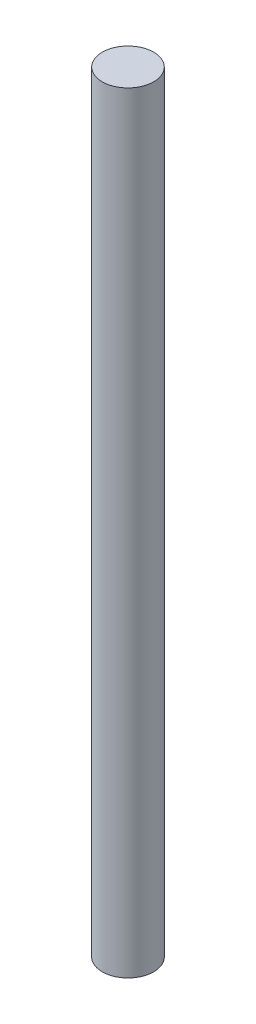
SolidWorks part; units mm, degrees
ref_plane "前视基准面" through (0, 0, 0) normal (0, 0, 1) x (1, 0, 0)
ref_plane "上视基准面" through (0, 0, 0) normal (0, 1, 0) x (1, 0, 0)
ref_plane "右视基准面" through (0, 0, 0) normal (1, 0, 0) x (0, 0, -1)
sketch "草图1" plane through (0, 0, 0) normal (0, 1, 0) x (1, 0, 0)
  circle A0 centre (0, 0) radius 4
  dimension "D1" = 8
extrude "凸台-拉伸1" add sketch "草图1" along normal blind 120
